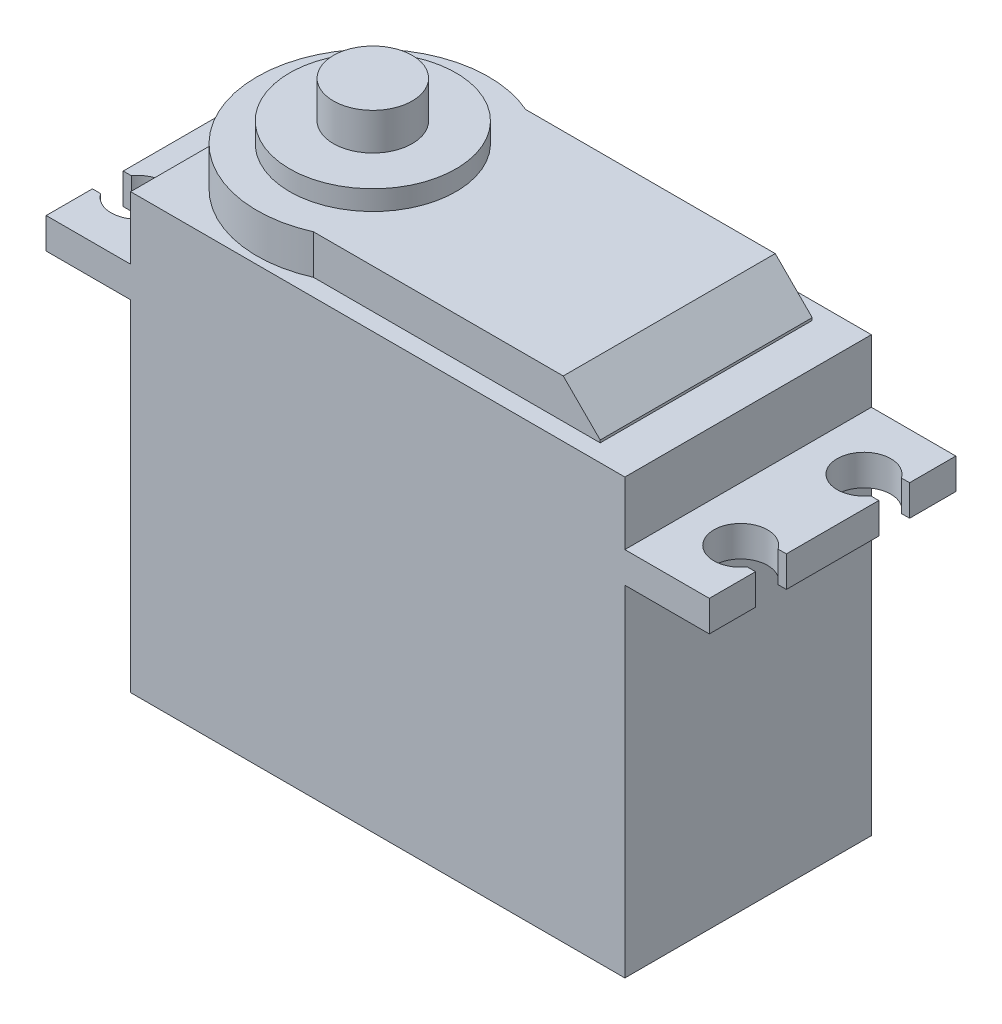
SolidWorks part; units mm, degrees
ref_plane "Plan de face" through (0, 0, 0) normal (0, 0, 1) x (1, 0, 0)
ref_plane "Plan de dessus" through (0, 0, 0) normal (0, 1, 0) x (1, 0, 0)
ref_plane "Plan de droite" through (0, 0, 0) normal (1, 0, 0) x (0, 0, -1)
sketch "Esquisse1" plane through (0, 0, 0) normal (0, 0, 1) x (1, 0, 0)
  line L0 (20.05, 41.402) -> (20.05, 0) construction
  line L1 (-6.366, 41.402) -> (46.466, 41.402) construction
  line L2 (-6.366, 41.402) -> (-6.366, 0) construction
  line L3 (-6.366, 0) -> (46.466, 0) construction
  line L4 (46.466, 41.402) -> (46.466, 0) construction
  line L5 (-6.366, 20.701) -> (46.466, 20.701) construction
  line L6 (0, 38.4) -> (36.7, 38.4) construction
  line L7 (0, 38.4) -> (40.1, 38.4) construction
  line L8 (0, 38.4) -> (0, 0) construction
  line L9 (0, 0) -> (40.1, 0)
  line L10 (40.1, 38.4) -> (40.1, 0) construction
  line L11 (40.1, 35.2) -> (40.1, 30.1)
  line L12 (36.7, 38.4) -> (36.7, 35.2)
  line L13 (40.1, 27.6) -> (40.1, 0)
  line L14 (0, 27.6) -> (-6.85, 27.6)
  line L15 (-6.85, 27.6) -> (-6.85, 30.1)
  line L16 (-6.85, 30.1) -> (0, 30.1)
  line L17 (40.1, 27.6) -> (46.95, 27.6)
  line L18 (46.95, 27.6) -> (46.95, 30.1)
  line L19 (46.95, 30.1) -> (40.1, 30.1)
  line L20 (36.7, 35.2) -> (40.1, 35.2)
  line L21 (9.652, 43) -> (9.652, 38.4) construction
  line L22 (0, 38.4) -> (0, 30.1)
  line L23 (2.902, 38.4) -> (2.902, 40)
  line L24 (2.902, 40) -> (16.402, 40) construction
  line L25 (16.402, 38.4) -> (16.402, 40)
  line L26 (0, 27.6) -> (0, 0)
  line L27 (6.452, 40) -> (6.452, 43)
  line L28 (6.452, 43) -> (12.852, 43)
  line L29 (12.852, 40) -> (12.852, 43)
  line L30 (2.902, 38.4) -> (0, 38.4)
  line L31 (12.852, 40) -> (16.402, 40)
  line L32 (16.402, 38.4) -> (36.7, 38.4)
  line L33 (2.902, 40) -> (6.452, 40)
  point P33 (9.652, 40)
  dimension "D1" = 52.832
  dimension "D2" = 41.402
  dimension "D3" = 40.1
  dimension "D4" = 38.4
  dimension "D5" = 2.5
  dimension "D6" = 27.6
  dimension "D7" = 36.7
  dimension "D8" = 35.2
  dimension "D9" = 12.9
  dimension "D11" = 9.652
  dimension "D12" = 53.8
  dimension "D13" = 13.5
  dimension "D14" = 6.4
  dimension "D15" = 40
extrude "Boss.-Extru.1" add sketch "Esquisse1" along normal blind 20
sketch "Esquisse2" plane through (0, 30.1, 0) normal (0, 1, 0) x (1, 0, 0)
  line L0 (-6.85, -10) -> (46.95, -10) construction
  line L1 (-6.85, -20) -> (-6.85, 0) construction
  line L2 (46.95, -20) -> (46.95, 0) construction
  line L3 (9.652, 0) -> (9.652, -20) construction
  line L4 (12.852, 0) -> (6.452, 0) construction
  line L5 (12.852, -20) -> (6.452, -20) construction
  line L6 (20.05, 0) -> (20.05, -20) construction
  line L7 (36.7, 0) -> (16.402, 0) construction
  line L8 (36.7, -20) -> (16.402, -20) construction
  line L9 (-6.85, -3.75) -> (-6.85, -6.25)
  line L10 (-6.85, -3.75) -> (-6.186, -3.75)
  line L11 (-6.85, -6.25) -> (-6.186, -6.25)
  line L12 (-4.4, -5) -> (-9.3387, -5) construction
  line L13 (46.95, -6.25) -> (46.286, -6.25)
  line L14 (46.95, -3.75) -> (46.95, -6.25)
  line L15 (46.95, -3.75) -> (46.286, -3.75)
  line L20 (46.95, -16.25) -> (46.286, -16.25)
  line L21 (46.95, -13.75) -> (46.286, -13.75)
  line L23 (46.95, -16.25) -> (46.95, -13.75)
  line L25 (-4.4, -15) -> (-9.3387, -15) construction
  line L26 (-6.85, -13.75) -> (-6.186, -13.75)
  line L27 (-6.85, -16.25) -> (-6.186, -16.25)
  line L30 (-6.85, -16.25) -> (-6.85, -13.75)
  arc A0 (-6.186, -6.25) -> (-6.186, -3.75) centre (-4.4, -5) ccw
  arc A1 (46.286, -6.25) -> (46.286, -3.75) centre (44.5, -5) cw
  arc A2 (46.286, -13.75) -> (46.286, -16.25) centre (44.5, -15) ccw
  arc A3 (-6.186, -13.75) -> (-6.186, -16.25) centre (-4.4, -15) cw
  dimension "D1" = 2.18
  dimension "D2" = 2.45
  dimension "D3" = 53.8
  dimension "D4" = 2.5
  dimension "D5" = 5
extrude "Enlèv. mat.-Extru.1" cut sketch "Esquisse2" against normal through all
sketch "Esquisse5" plane through (0, 43, 0) normal (0, 1, 0) x (1, 0, 0)
  line L0 (-6.85, -10) -> (46.95, -10) construction
  line L1 (-6.85, -13.75) -> (-6.85, -6.25) construction
  line L2 (46.95, -13.75) -> (46.95, -6.25) construction
  line L3 (6.452, -20) -> (6.452, 0) construction
  line L4 (12.852, -20) -> (12.852, 0) construction
  line L6 (-6.85, 0) -> (46.95, 0)
  line L7 (-6.85, 0) -> (-6.85, -20)
  line L8 (-6.85, -20) -> (46.95, -20)
  line L9 (46.95, 0) -> (46.95, -20)
  circle A0 centre (9.652, -10) radius 3.2
extrude "Enlèv. mat.-Extru.2" cut sketch "Esquisse5" against normal up to vertex (3 mm away) up to point (12.852, 40, 20)
sketch "Esquisse6" plane through (0, 40, 0) normal (0, 1, 0) x (1, 0, 0)
  line L0 (16.402, -20) -> (16.402, 0) construction
  line L2 (-6.85, 0) -> (46.95, 0)
  line L3 (-6.85, 0) -> (-6.85, -20)
  line L4 (-6.85, -20) -> (46.95, -20)
  line L5 (46.95, 0) -> (46.95, -20)
  circle A0 centre (9.652, -10) radius 6.75
extrude "Enlèv. mat.-Extru.3" cut sketch "Esquisse6" against normal up to vertex (1.6 mm away) up to point (16.402, 38.4, 20)
sketch "Esquisse7" plane through (0, 38.4, 0) normal (0, 1, 0) x (1, 0, 0)
  line L0 (36.7, -1.4) -> (13.4467, -1.4) construction
  line L1 (36.7, -20) -> (36.7, 0) construction
  line L2 (36.7, -18.6) -> (13.4467, -18.6) construction
  line L3 (36.7, -20) -> (36.7, 0) construction
  line L4 (9.652, -10) -> (46.95, -10) construction
  line L5 (46.95, -13.75) -> (46.95, -6.25) construction
  line L6 (13.4467, -18.6) -> (36.7, -18.6)
  line L7 (36.7, -18.6) -> (36.7, -1.4)
  line L8 (36.7, -1.4) -> (13.4467, -1.4)
  line L10 (-6.85, 0) -> (46.95, 0)
  line L11 (-6.85, 0) -> (-6.85, -20)
  line L12 (-6.85, -20) -> (46.95, -20)
  line L13 (46.95, 0) -> (46.95, -20)
  circle A0 centre (9.652, -10) radius 9.4 construction
  arc A1 (13.4467, -1.4) -> (13.4467, -18.6) centre (9.652, -10) ccw
  dimension "D1" = 18.8
  dimension "D2" = 17.2
extrude "Enlèv. mat.-Extru.4" cut sketch "Esquisse7" against normal up to vertex (3.2 mm away)
chamfer "Chanfrein2" distance 3 angle 45 1 edges at (36.7, 38.4, 10)
